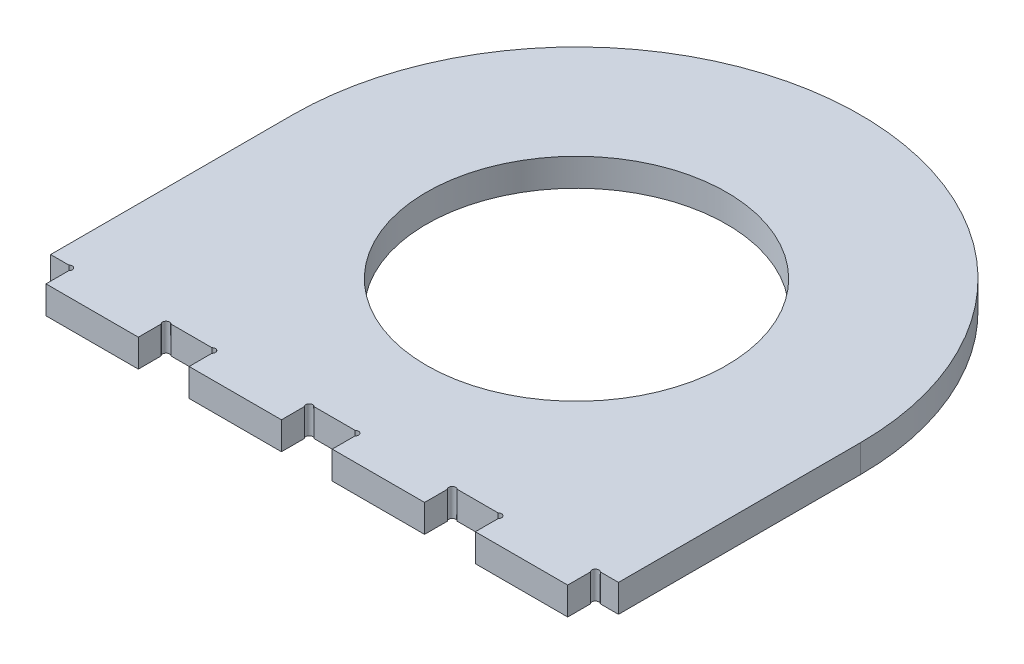
SolidWorks part; units mm, degrees
ref_plane "Alzado" through (0, 0, 0) normal (0, 0, 1) x (1, 0, 0)
ref_plane "Planta" through (0, 0, 0) normal (0, 1, 0) x (1, 0, 0)
ref_plane "Vista lateral" through (0, 0, 0) normal (1, 0, 0) x (0, 0, -1)
sketch "Croquis1" plane through (0, 0, 0) normal (0, 1, 0) x (1, 0, 0)
  line L0 (57, 0) -> (57, 104.8203)
  line L1 (295.1213, 0) -> (303, 0)
  line L2 (303, 0) -> (303, 104.8203)
  line L6 (67, -2.1213) -> (67, -12)
  line L7 (67, -12) -> (107, -12)
  line L8 (107, -12) -> (107, -2.1213)
  line L9 (129, -2.1213) -> (129, -12)
  line L10 (129, -12) -> (169, -12)
  line L11 (169, -12) -> (169, -2.1213)
  line L12 (191, -2.1213) -> (191, -12)
  line L13 (191, -12) -> (231, -12)
  line L14 (231, -12) -> (231, -2.1213)
  line L15 (253, -2.1213) -> (253, -12)
  line L16 (253, -12) -> (293, -12)
  line L17 (293, -12) -> (293, -2.1213)
  line L21 (57, 0) -> (64.8787, 0)
  line L22 (109.1213, 0) -> (126.8787, 0)
  line L23 (171.1213, 0) -> (188.8787, 0)
  line L24 (233.1213, 0) -> (250.8787, 0)
  circle A0 centre (180, 104.8203) radius 65
  arc A1 (303, 104.8203) -> (57, 104.8203) centre (180, 104.8203) ccw
  arc A2 (109.1213, 0) -> (107, -2.1213) centre (108.0607, -1.0607) ccw
  arc A3 (129, -2.1213) -> (126.8787, 0) centre (127.9393, -1.0607) ccw
  arc A4 (67, -2.1213) -> (64.8787, 0) centre (65.9393, -1.0607) ccw
  arc A5 (171.1213, 0) -> (169, -2.1213) centre (170.0607, -1.0607) ccw
  arc A6 (191, -2.1213) -> (188.8787, 0) centre (189.9393, -1.0607) ccw
  arc A7 (233.1213, 0) -> (231, -2.1213) centre (232.0607, -1.0607) ccw
  arc A8 (253, -2.1213) -> (250.8787, 0) centre (251.9393, -1.0607) ccw
  arc A9 (295.1213, 0) -> (293, -2.1213) centre (294.0607, -1.0607) ccw
  dimension "D2" = 246
  dimension "D5" = 22
  dimension "D6" = 22
  dimension "D7" = 22
extrude "Saliente-Extruir2" add sketch "Croquis1" along normal blind 12
